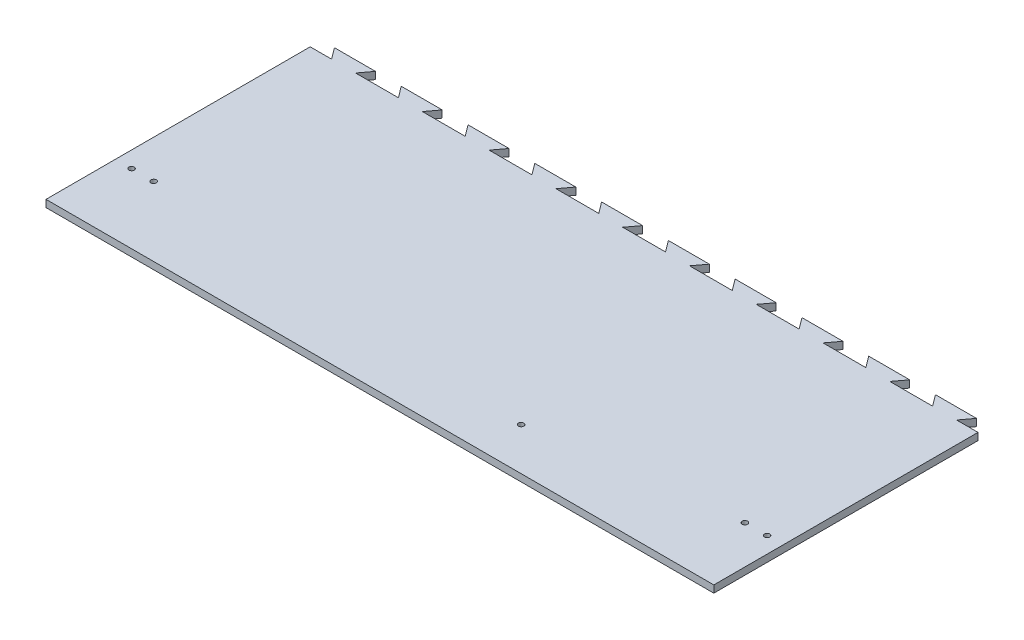
SolidWorks part; units mm, degrees
material "Multistrato di pioppo"
ref_plane "Piano frontale" through (0, 0, 0) normal (0, 0, 1) x (1, 0, 0)
ref_plane "Piano superiore" through (0, 0, 0) normal (0, 1, 0) x (1, 0, 0)
ref_plane "Piano destro" through (0, 0, 0) normal (1, 0, 0) x (0, 0, -1)
sketch "Schizzo1" plane through (0, 0, 0) normal (0, 1, 0) x (1, 0, 0)
  line L1 (-279, 220.75) -> (279, 220.75)
  line L2 (-279, 220.75) -> (-279, -220.75)
  line L3 (-279, -220.75) -> (279, -220.75)
  line L4 (279, 220.75) -> (279, -220.75)
  line L5 (-279, 220.75) -> (279, -220.75) construction
  line L6 (-279, -220.75) -> (279, 220.75) construction
  point P4 (0, 0)
  dimension "D1" = 558
  dimension "D2" = 441.5
extrude "Estrusione-Estrusione1" add sketch "Schizzo1" along normal blind 6
sketch "Schizzo2" plane through (0, 0, 0) normal (0, -1, 0) x (-1, 0, 0)
  circle A0 centre (-221, 207.25) radius 2.25
  circle A1 centre (-221, 188.75) radius 2.25
  circle A2 centre (-247, 162.75) radius 2.25
  circle A3 centre (-265.5, 162.75) radius 2.25
  circle A4 centre (221, 207.25) radius 2.25
  circle A5 centre (221, 188.75) radius 2.25
  circle A6 centre (247, 162.75) radius 2.25
  circle A7 centre (265.5, 162.75) radius 2.25
  circle A8 centre (265.5, -162.75) radius 2.25
  circle A9 centre (247, -162.75) radius 2.25
  circle A10 centre (-265.5, -162.75) radius 2.25
  circle A11 centre (-247, -162.75) radius 2.25
  circle A12 centre (-82.5, -185.25) radius 2.25
  dimension "D1" = 4.5
extrude "Taglio-Estrusione1" cut sketch "Schizzo2" against normal blind 10
sketch "Schizzo3" plane through (0, 6, 0) normal (0, 1, 0) x (1, 0, 0)
  line L0 (-279, 0) -> (-261.1, 0)
  line L1 (-279, 220.75) -> (-279, -220.75) construction
  line L2 (-261.1, 0) -> (-268.6, 10) construction
  line L3 (-268.6, 10) -> (-233.6, 10) construction
  line L4 (-233.6, 10) -> (-241.1, 0) construction
  line L5 (-241.1, 0) -> (-223.2, 0)
  line L6 (-261.1, 0) -> (-241.1, 0) construction
  line L7 (-251.1, 0) -> (-251.1, 10) construction
  line L8 (-279, 0) -> (-279, 220.75)
  line L9 (-279, 220.75) -> (279, 220.75)
  line L10 (-223.2, 0) -> (-205.3, 0)
  line L11 (-205.3, 0) -> (-212.8, 10) construction
  line L12 (-212.8, 10) -> (-177.8, 10) construction
  line L13 (-177.8, 10) -> (-185.3, 0) construction
  line L14 (-185.3, 0) -> (-167.4, 0)
  line L15 (-205.3, 0) -> (-185.3, 0) construction
  line L16 (-195.3, 0) -> (-195.3, 10) construction
  line L17 (-167.4, 0) -> (-149.5, 0)
  line L18 (-149.5, 0) -> (-157, 10) construction
  line L19 (-157, 10) -> (-122, 10) construction
  line L20 (-122, 10) -> (-129.5, 0) construction
  line L21 (-129.5, 0) -> (-111.6, 0)
  line L22 (-149.5, 0) -> (-129.5, 0) construction
  line L23 (-139.5, 0) -> (-139.5, 10) construction
  line L24 (-111.6, 0) -> (-93.7, 0)
  line L25 (-93.7, 0) -> (-101.2, 10) construction
  line L26 (-101.2, 10) -> (-66.2, 10) construction
  line L27 (-66.2, 10) -> (-73.7, 0) construction
  line L28 (-73.7, 0) -> (-55.8, 0)
  line L29 (-93.7, 0) -> (-73.7, 0) construction
  line L30 (-83.7, 0) -> (-83.7, 10) construction
  line L31 (-55.8, 0) -> (-37.9, 0)
  line L32 (-37.9, 0) -> (-45.4, 10) construction
  line L33 (-45.4, 10) -> (-10.4, 10) construction
  line L34 (-10.4, 10) -> (-17.9, 0) construction
  line L35 (-17.9, 0) -> (0, 0)
  line L36 (-37.9, 0) -> (-17.9, 0) construction
  line L37 (-27.9, 0) -> (-27.9, 10) construction
  line L38 (0, 0) -> (17.9, 0)
  line L39 (17.9, 0) -> (10.4, 10) construction
  line L40 (10.4, 10) -> (45.4, 10) construction
  line L41 (45.4, 10) -> (37.9, 0) construction
  line L42 (37.9, 0) -> (55.8, 0)
  line L43 (17.9, 0) -> (37.9, 0) construction
  line L44 (27.9, 0) -> (27.9, 10) construction
  line L45 (55.8, 0) -> (73.7, 0)
  line L46 (73.7, 0) -> (66.2, 10) construction
  line L47 (66.2, 10) -> (101.2, 10) construction
  line L48 (101.2, 10) -> (93.7, 0) construction
  line L49 (93.7, 0) -> (111.6, 0)
  line L50 (73.7, 0) -> (93.7, 0) construction
  line L51 (83.7, 0) -> (83.7, 10) construction
  line L52 (111.6, 0) -> (129.5, 0)
  line L53 (129.5, 0) -> (122, 10) construction
  line L54 (122, 10) -> (157, 10) construction
  line L55 (157, 10) -> (149.5, 0) construction
  line L56 (149.5, 0) -> (167.4, 0)
  line L57 (129.5, 0) -> (149.5, 0) construction
  line L58 (139.5, 0) -> (139.5, 10) construction
  line L59 (167.4, 0) -> (185.3, 0)
  line L60 (185.3, 0) -> (177.8, 10) construction
  line L61 (177.8, 10) -> (212.8, 10) construction
  line L62 (212.8, 10) -> (205.3, 0) construction
  line L63 (205.3, 0) -> (223.2, 0)
  line L64 (185.3, 0) -> (205.3, 0) construction
  line L65 (195.3, 0) -> (195.3, 10) construction
  line L66 (223.2, 0) -> (241.1, 0)
  line L67 (241.1, 0) -> (233.6, 10) construction
  line L68 (233.6, 10) -> (268.6, 10) construction
  line L69 (268.6, 10) -> (261.1, 0) construction
  line L70 (261.1, 0) -> (279, 0)
  line L71 (241.1, 0) -> (261.1, 0) construction
  line L72 (251.1, 0) -> (251.1, 10) construction
  line L73 (279, -220.75) -> (279, 220.75) construction
  line L74 (279, 220.75) -> (279, 0)
  line L75 (-268.225, 9.5) -> (-233.975, 9.5)
  line L76 (-212.425, 9.5) -> (-178.175, 9.5)
  line L77 (-156.625, 9.5) -> (-122.375, 9.5)
  line L78 (-100.825, 9.5) -> (-66.575, 9.5)
  line L79 (-45.025, 9.5) -> (-10.775, 9.5)
  line L80 (10.775, 9.5) -> (45.025, 9.5)
  line L81 (66.575, 9.5) -> (100.825, 9.5)
  line L82 (122.375, 9.5) -> (156.625, 9.5)
  line L83 (178.175, 9.5) -> (212.425, 9.5)
  line L84 (233.975, 9.5) -> (268.225, 9.5)
  line L85 (261.1, 0) -> (268.225, 9.5)
  line L86 (241.1, 0) -> (233.975, 9.5)
  line L87 (205.3, 0) -> (212.425, 9.5)
  line L88 (185.3, 0) -> (178.175, 9.5)
  line L89 (149.5, 0) -> (156.625, 9.5)
  line L90 (129.5, 0) -> (122.375, 9.5)
  line L91 (93.7, 0) -> (100.825, 9.5)
  line L92 (73.7, 0) -> (66.575, 9.5)
  line L93 (37.9, 0) -> (45.025, 9.5)
  line L94 (17.9, 0) -> (10.775, 9.5)
  line L95 (-17.9, 0) -> (-10.775, 9.5)
  line L96 (-37.9, 0) -> (-45.025, 9.5)
  line L97 (-73.7, 0) -> (-66.575, 9.5)
  line L98 (-93.7, 0) -> (-100.825, 9.5)
  line L99 (-129.5, 0) -> (-122.375, 9.5)
  line L100 (-149.5, 0) -> (-156.625, 9.5)
  line L101 (-185.3, 0) -> (-178.175, 9.5)
  line L102 (-205.3, 0) -> (-212.425, 9.5)
  line L103 (-241.1, 0) -> (-233.975, 9.5)
  line L104 (-261.1, 0) -> (-268.225, 9.5)
  dimension "D1" = 55.8
  dimension "D2" = 35
  dimension "D3" = 20
  dimension "D4" = 10
  dimension "D6" = 0.5
  dimension "D5" = 10
extrude "Taglio-Estrusione2" cut sketch "Schizzo3" against normal blind 10
